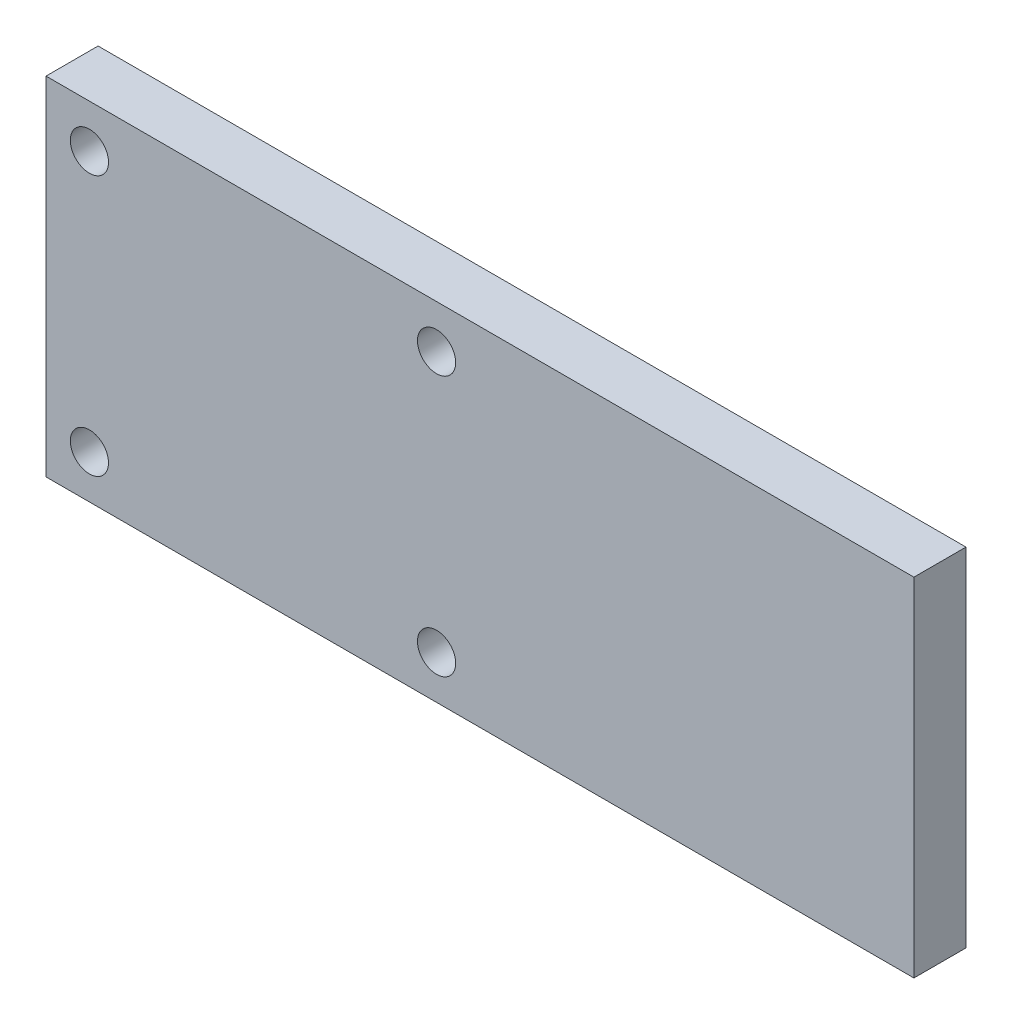
SolidWorks part; units mm, degrees
ref_plane "Front Plane" through (0, 0, 0) normal (0, 0, 1) x (1, 0, 0)
ref_plane "Top Plane" through (0, 0, 0) normal (0, 1, 0) x (1, 0, 0)
ref_plane "Right Plane" through (0, 0, 0) normal (1, 0, 0) x (0, 0, -1)
ref_plane "Plane1" through (0, 0, 9) normal (0, 0, 1) x (1, 0, 0)
sketch "Sketch1" plane through (0, 0, 9) normal (0, 0, 1) x (1, 0, 0)
  line L0 (15, 54) -> (15, 14)
  line L1 (15, 14) -> (115, 14)
  line L2 (115, 14) -> (115, 54)
  line L3 (115, 54) -> (15, 54)
  circle A0 centre (60, 49) radius 2.2
  circle A1 centre (20, 19) radius 2.2
  circle A2 centre (20, 49) radius 2.2
  circle A3 centre (60, 19) radius 2.2
extrude "Boss-Extrude1" add sketch "Sketch1" against normal blind 6
